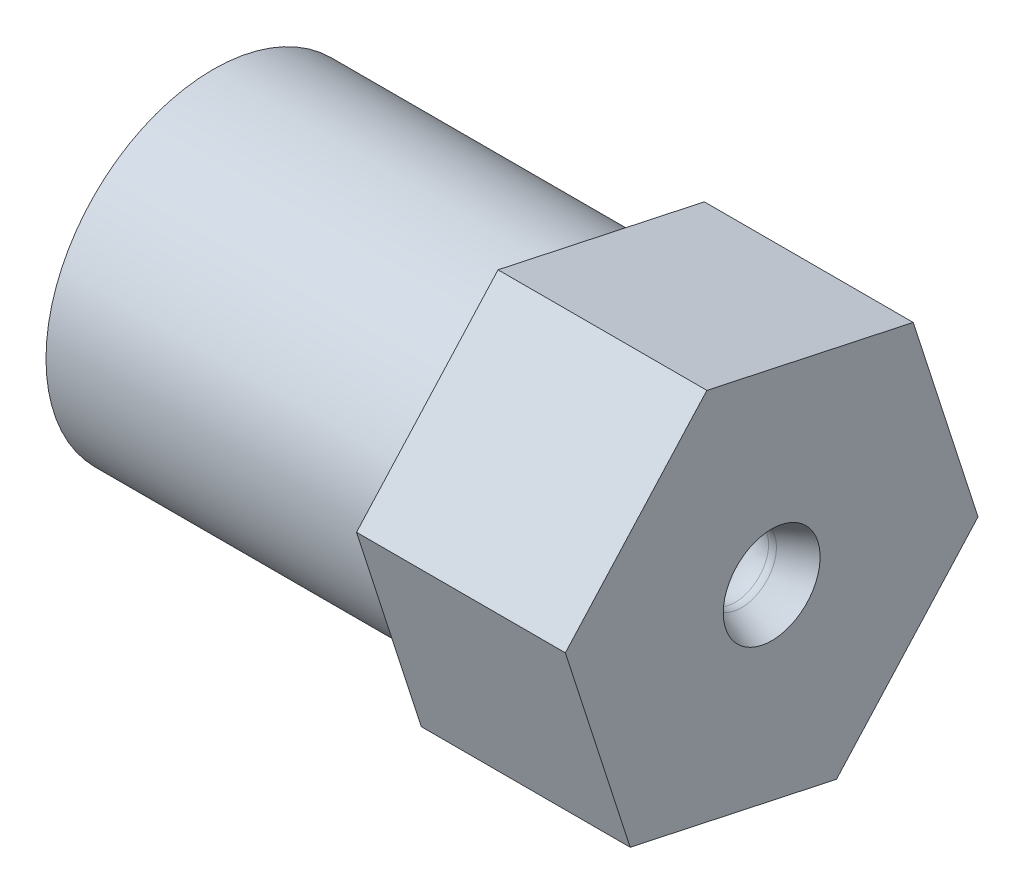
SolidWorks part; units mm, degrees
ref_plane "Front Plane" through (0, 0, 0) normal (0, 0, 1) x (1, 0, 0)
ref_plane "Top Plane" through (0, 0, 0) normal (0, 1, 0) x (1, 0, 0)
ref_plane "Right Plane" through (0, 0, 0) normal (1, 0, 0) x (0, 0, -1)
sketch "Sketch1" plane through (0, 0, 0) normal (0, 0, 1) x (1, 0, 0)
  line L0 (0, 0) -> (2.2194, 0) construction
  line L1 (0.3816, 2.1271) -> (2.2194, 3.1043) construction
  line L2 (-2.1553, 2.9247) -> (-2.7456, 3.5151)
  line L3 (-31.75, 4.445) -> (-31.75, 10.16) construction
  line L4 (-4.9907, 4.445) -> (-31.75, 4.445) construction
  line L5 (-31.75, 10.16) -> (-10.4806, 10.16)
  line L6 (2.2194, 10.16) -> (2.2194, 2.9446)
  line L7 (2.2194, 2.9446) -> (12.3917, 6.6471) construction
  line L8 (-10.4806, 10.16) -> (2.2194, 10.16)
  line L9 (-4.9907, 4.445) -> (-13.462, 4.445)
  line L10 (-19.939, 5.461) -> (-19.939, 6.8199)
  line L11 (-20.066, 6.9469) -> (-24.892, 6.9469)
  line L12 (-24.892, 6.9469) -> (-24.892, 7.8994)
  line L13 (-25.019, 8.0264) -> (-31.115, 8.0264)
  line L14 (-31.75, 10.16) -> (-31.75, 8.6614)
  line L15 (0, 0) -> (-31.75, 0) construction
  line L16 (-13.462, 4.445) -> (-13.462, 4.699)
  line L17 (-13.589, 4.826) -> (-19.304, 4.826)
  arc A0 (-2.1553, 2.9247) -> (0, 2.032) centre (0, 5.08) ccw
  arc A1 (0, 2.032) -> (0.3816, 2.1271) centre (0, 2.8448) ccw
  arc A2 (-2.7456, 3.5151) -> (-4.9907, 4.445) centre (-4.9907, 1.27) ccw
  arc A3 (-31.115, 8.0264) -> (-31.75, 8.6614) centre (-31.115, 8.6614) cw
  arc A4 (-19.304, 4.826) -> (-19.939, 5.461) centre (-19.304, 5.461) cw
  arc A5 (-13.462, 4.699) -> (-13.589, 4.826) centre (-13.589, 4.699) ccw
  arc A6 (-19.939, 6.8199) -> (-20.066, 6.9469) centre (-20.066, 6.8199) ccw
  arc A7 (-24.892, 7.8994) -> (-25.019, 8.0264) centre (-25.019, 7.8994) ccw
  parabola Q0 (2.2194, 2.9446) -> (0.3816, 2.1271) focus (3.7329, -4.1758) apex (0.3816, 2.1271)
  point P30 (-31.75, 8.0264)
  point P39 (-24.892, 8.0264)
  dimension "D3" = 3.048
  dimension "D4" = 0.8128
  dimension "D11" = 3.175
  dimension "D12" = 20
  dimension "D14" = 6.9469
  dimension "D20" = 0.635
  dimension "D21" = 0.127
  dimension "D2" = 2.2194
  dimension "D5" = 2.9446
  dimension "D6" = 28
  dimension "D7" = 45
  dimension "D8" = 8.0264
  dimension "D9" = 31.75
  dimension "D10" = 10.16
  dimension "D13" = 12.7
  dimension "D15" = 4.445
  dimension "D16" = 6.858
  dimension "D17" = 11.811
  dimension "D18" = 18.288
  dimension "D19" = 4.826
  dimension "D22" = 2.032
revolve "Revolve1" add sketch "Sketch1" angle 360 about L0
sketch "Sketch4" plane through (2.2194, 0, 0) normal (1, 0, 0) x (0, 0, -1)
  line L1 (3.9404, -12.2116) -> (12.5458, -2.6933)
  line L2 (12.5458, -2.6933) -> (8.6054, 9.5183)
  line L3 (8.6054, 9.5183) -> (-3.9404, 12.2116)
  line L4 (-3.9404, 12.2116) -> (-12.5458, 2.6933)
  line L5 (-12.5458, 2.6933) -> (-8.6054, -9.5183)
  line L6 (-8.6054, -9.5183) -> (3.9404, -12.2116)
  circle A0 centre (0, 0) radius 10.16
  circle A1 centre (0, 0) radius 10.16 construction
  circle A2 centre (0, 0) radius 11.1125 construction
  circle M1 centre (0, 0) radius 10.16
  dimension "D1" = 22.225
extrude "Boss-Extrude1" add sketch "Sketch4" against normal blind 12.7 contours L4 L5 M1 | L3 L4 M1 | L2 L3 M1 | L1 L2 M1 | L6 L1 M1 | L5 L6 M1
fillet "Fillet1" radius 0.635 1 edges at (-10.4806, 0, -10.16)
equation "\"D3@Sketch1\" = 1.5 * \"D22@Sketch1\""
equation "\"D4@Sketch1\"  = .4 * \"D22@Sketch1\""
equation "\"D5@Sketch1\"=\"D22@Sketch1\" * ( \"er\") ^ .5"
equation "\"er\"= 2.1"
